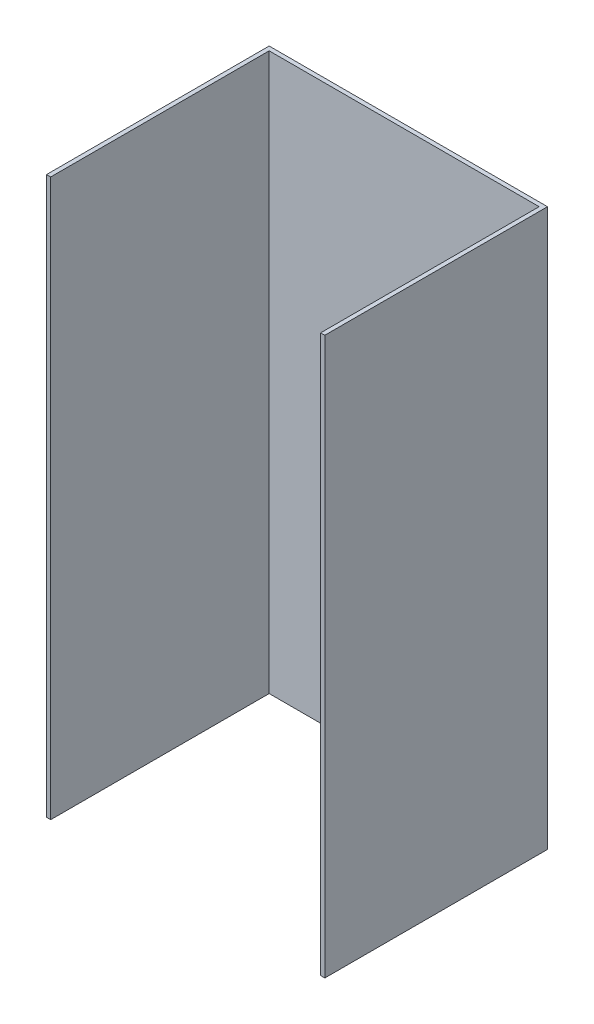
SolidWorks part; units mm, degrees
ref_plane "Front Plane" through (0, 0, 0) normal (0, 0, 1) x (1, 0, 0)
ref_plane "Top Plane" through (0, 0, 0) normal (0, 1, 0) x (1, 0, 0)
ref_plane "Right Plane" through (0, 0, 0) normal (1, 0, 0) x (0, 0, -1)
sketch "Sketch1" plane through (0, 0, 0) normal (0, 0, 1) x (1, 0, 0)
  line L1 (50, -100) -> (-50, -100)
  line L2 (50, -100) -> (50, 100)
  line L3 (50, 100) -> (-50, 100)
  line L4 (-50, -100) -> (-50, 100)
  line L5 (50, -100) -> (-50, 100) construction
  line L6 (50, 100) -> (-50, -100) construction
  point P0 (0, 0)
  dimension "D1" = 100
  dimension "D2" = 200
extrude "Boss-Extrude1" add sketch "Sketch1" along normal blind 80
shell "Shell1" thickness 1.5
